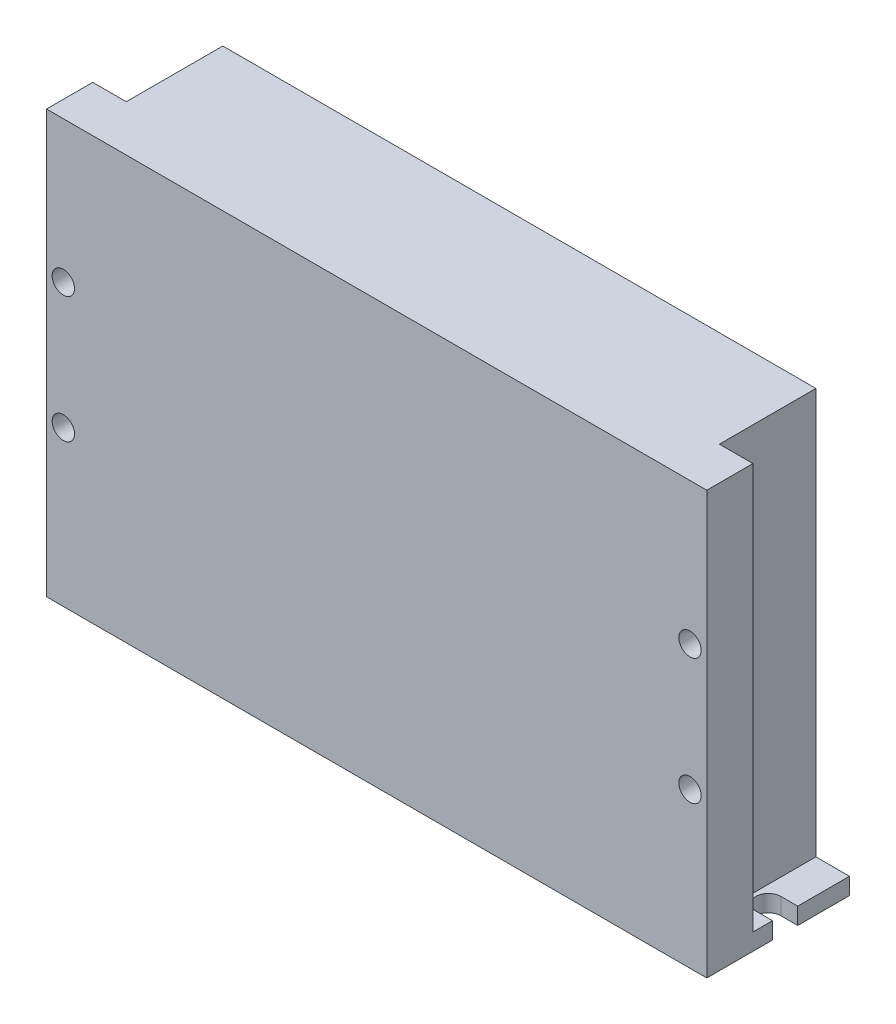
SolidWorks part; units mm, degrees
ref_plane "前视基准面" through (0, 0, 0) normal (0, 0, 1) x (1, 0, 0)
ref_plane "上视基准面" through (0, 0, 0) normal (0, 1, 0) x (1, 0, 0)
ref_plane "右视基准面" through (0, 0, 0) normal (1, 0, 0) x (0, 0, -1)
sketch "草图1" plane through (0, 0, 0) normal (0, 1, 0) x (1, 0, 0)
  line L1 (0, 0) -> (118, 0)
  line L2 (0, 0) -> (0, -25.5)
  line L3 (0, -25.5) -> (118, -25.5)
  line L4 (118, 0) -> (118, -25.5)
  dimension "D1" = 118
  dimension "D2" = 25.5
extrude "凸台-拉伸1" add sketch "草图1" along normal blind 75.5
sketch "草图2" plane through (0, 75.5, 0) normal (0, 1, 0) x (1, 0, 0)
  line L0 (0, -25.5) -> (118, -25.5) construction
  line L3 (0, -17.25) -> (6, -17.25)
  line L6 (0, 0) -> (0, -25.5) construction
  line L7 (6, -17.25) -> (6, 0)
  line L8 (118, 0) -> (0, 0) construction
  line L9 (6, 0) -> (0, 0)
  line L10 (0, 0) -> (0, -17.25)
  line L11 (118, -25.5) -> (118, 0) construction
  line L12 (118, 0) -> (112, 0)
  line L13 (118, 0) -> (118, -17.25)
  line L14 (118, -17.25) -> (112, -17.25)
  line L15 (112, 0) -> (112, -17.25)
  dimension "D1" = 8.25
  dimension "D2" = 6
  dimension "D3" = 6
  dimension "D4" = 8.25
extrude "切除-拉伸1" cut sketch "草图2" against normal blind 72.5
sketch "草图3" plane through (0, 3, 0) normal (0, 1, 0) x (1, 0, 0)
  line L0 (0, 0) -> (0, -17.25) construction
  line L1 (0, -13.75) -> (3, -13.75)
  line L2 (0, -13.75) -> (0, -9.25)
  line L3 (0, -9.25) -> (3, -9.25)
  line L4 (3, -13.75) -> (3, -9.25) construction
  line L5 (0, -25.5) -> (118, -25.5) construction
  line L6 (59, -25.5) -> (59, 16.7892) construction
  line L7 (118, -13.75) -> (118, -9.25)
  line L8 (118, -13.75) -> (115, -13.75)
  line L9 (118, -9.25) -> (115, -9.25)
  arc A0 (3, -13.75) -> (3, -9.25) centre (3, -11.5) ccw
  arc A1 (115, -13.75) -> (115, -9.25) centre (115, -11.5) cw
  point P6 (0, -11.5)
  dimension "D1" = 14
  dimension "D2" = 4.5
  dimension "D3" = 3
extrude "切除-拉伸2" cut sketch "草图3" against normal through all
sketch "草图4" plane through (0, 0, 17.25) normal (0, 0, -1) x (-1, 0, 0)
  line L0 (-112, 75.5) -> (-118, 75.5) construction
  line L1 (0, 75.5) -> (-6, 75.5) construction
  line L3 (-112, 75.5) -> (-6, 75.5) construction
  line L4 (-112, 3) -> (-112, 75.5) construction
  line L5 (-112, 3) -> (-112, 75.5) construction
  line L6 (-6, 3) -> (-6, 75.5) construction
  circle A0 centre (-115, 50.2) radius 2
  circle A1 centre (-115, 27.7) radius 2
  circle A2 centre (-3, 50.2) radius 2
  circle A3 centre (-3, 27.7) radius 2
  dimension "D5" = 4
  dimension "D1" = 25.3
  dimension "D2" = 25.3
  dimension "D3" = 47.8
  dimension "D4" = 47.8
  dimension "D6" = 3
  dimension "D7" = 3
  dimension "D8" = 3
  dimension "D9" = 3
extrude "切除-拉伸3" cut sketch "草图4" against normal through all
